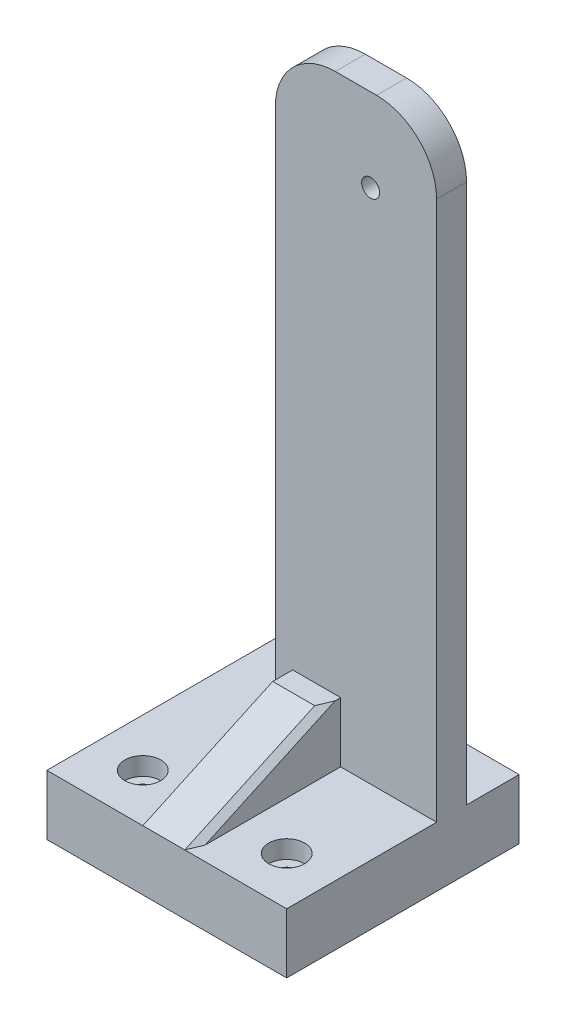
SolidWorks part; units mm, degrees
ref_plane "Front Plane" through (0, 0, 0) normal (0, 0, 1) x (1, 0, 0)
ref_plane "Top Plane" through (0, 0, 0) normal (0, 1, 0) x (1, 0, 0)
ref_plane "Right Plane" through (0, 0, 0) normal (1, 0, 0) x (0, 0, -1)
sketch "Sketch1" plane through (0, 0, 0) normal (0, 1, 0) x (1, 0, 0)
  line L1 (-20, -15) -> (20, -15)
  line L2 (-20, -15) -> (-20, 15)
  line L3 (-20, 15) -> (20, 15)
  line L4 (20, -15) -> (20, 15)
  line L5 (-20, -15) -> (20, 15) construction
  line L6 (-20, 15) -> (20, -15) construction
  line L7 (-20, 15) -> (20, 15)
  line L8 (-20, 15) -> (-20, 9.2)
  line L9 (-20, 9.2) -> (20, 9.2)
  line L10 (20, 15) -> (20, 9.2)
  point P0 (0, 0)
  dimension "D1" = 40
  dimension "D2" = 30
extrude "Boss-Extrude1" add sketch "Sketch1" along normal blind 10 contours L9 L2 L1 L4 | L2 L9 L4 L3
sketch "Sketch2" plane through (0, 10, 0) normal (0, 1, 0) x (1, 0, 0)
  line L0 (20, -15) -> (20, 15) construction
  line L1 (-6.8887, 15) -> (20, 15)
  line L2 (-6.8887, 15) -> (-6.8887, 10)
  line L3 (-6.8887, 10) -> (20, 10)
  line L4 (20, 15) -> (20, 10)
  line L5 (-20, 15) -> (20, 15) construction
  dimension "D1" = 5
  dimension "D2" = 0
extrude "Boss-Extrude2" add sketch "Sketch2" along normal blind 100
sketch "Sketch3" plane through (0, 0, -10) normal (0, 0, 1) x (1, 0, 0)
  line L1 (20, 110) -> (20, 10) construction
  line L2 (-6.8887, 10) -> (20, 10) construction
  circle A0 centre (9, 96.14) radius 1.5
  dimension "D1" = 3
  dimension "D2" = 86.14
  dimension "D3" = 11
extrude "Cut-Extrude1" cut sketch "Sketch3" against normal blind 30
sketch "Sketch6" plane through (0, 10, 0) normal (0, 1, 0) x (1, 0, 0)
  line L0 (-6.8887, 10) -> (20, 10) construction
  line L1 (-4, 10) -> (4, 10)
  line L2 (-4, 10) -> (-4, -15)
  line L3 (-4, -15) -> (4, -15)
  line L4 (4, 10) -> (4, -15)
  line L5 (-20, -15) -> (20, -15) construction
  line L6 (20, -15) -> (20, 10) construction
  line L7 (-20, -15) -> (-20, 15) construction
  dimension "D1" = 16
  dimension "D2" = 16
extrude "Boss-Extrude3" add sketch "Sketch6" along normal blind 10
sketch "Sketch7" plane through (-4, 0, 0) normal (-1, 0, 0) x (0, 0, 1)
  line L0 (-10, 21.5351) -> (15, 10)
  line L2 (-10, 21.5351) -> (15, 21.5351)
  line L3 (15, 21.5351) -> (15, 10)
  line L4 (-10, 20) -> (-10, 10) construction
  line L5 (15, 20) -> (15, 10) construction
extrude "Cut-Extrude4" cut sketch "Sketch7" against normal blind 35
sketch "Sketch8" plane through (0, 0, 0) normal (0, 1, 0) x (1, 0, 0)
  line L0 (-20, 15) -> (4, 15)
  line L1 (-20, 15) -> (4, 15)
  line L2 (-20, 15) -> (-20, 30)
  line L3 (-20, 30) -> (4, 30)
  line L4 (4, 15) -> (4, 30)
  line L6 (20, 15) -> (4, 15)
  line L7 (1.6425, 29.4411) -> (1.5198, 29.4411)
  line L8 (20, 15) -> (20, 23.7683)
  line L9 (20, 23.7683) -> (4, 23.7683)
  line L10 (4, 15) -> (4, 23.7683)
  dimension "D1" = 15
  dimension "D2" = 24
extrude "Boss-Extrude4" add sketch "Sketch8" along normal blind 10
sketch "Sketch9" plane through (0, 10, 0) normal (0, 1, 0) x (1, 0, 0)
  line L0 (-6.8887, 15) -> (20, 15) construction
  line L1 (-4, 15) -> (4, 15)
  line L2 (-4, 15) -> (-4, 30)
  line L3 (-4, 30) -> (4, 30)
  line L4 (4, 15) -> (4, 30)
extrude "Boss-Extrude5" add sketch "Sketch9" along normal blind 30
sketch "Sketch10" plane through (-4, 0, 0) normal (-1, 0, 0) x (0, 0, 1)
  line L0 (-30, 10) -> (-20.1868, 40)
  line L1 (-30, 40) -> (-15, 40) construction
  line L2 (-20.1868, 40) -> (-30, 40)
  line L3 (-30, 40) -> (-30, 10)
extrude "Cut-Extrude5" cut sketch "Sketch10" against normal blind 35
sketch "Sketch11" plane through (0, 10, 0) normal (0, 1, 0) x (1, 0, 0)
  line L0 (-20, -15) -> (-4, -15) construction
  line L1 (4, -15) -> (20, -15) construction
  line L2 (-20, -15) -> (-20, 30) construction
  line L3 (20, -15) -> (20, 10) construction
  circle A0 centre (-12, -7) radius 1.42
  circle A1 centre (12, -7) radius 1.42
  circle A2 centre (-12, 23) radius 1.42
  dimension "D1" = 2.84
  dimension "D2" = 2.84
  dimension "D3" = 2.84
  dimension "D4" = 30
  dimension "D5" = 8
  dimension "D6" = 8
  dimension "D7" = 8
  dimension "D8" = 8
extrude "Cut-Extrude6" cut sketch "Sketch11" against normal blind 20
sketch "Sketch12" plane through (0, 10, 0) normal (0, 1, 0) x (1, 0, 0)
  circle A0 centre (-12, -7) radius 3
  circle A1 centre (12, -7) radius 3
  circle A2 centre (-12, 23) radius 3
  dimension "D1" = 6
  dimension "D2" = 6
  dimension "D3" = 6
extrude "Cut-Extrude7" cut sketch "Sketch12" against normal blind 3
fillet "Fillet1" radius 10 2 edges at (20, 110, -12.5) (-6.8887, 110, -12.5)
chamfer "Chamfer1" distance 1 angle 45 2 edges at (4, 25, -25.0934) (-4, 25, -25.0934)
chamfer "Chamfer2" distance 1 angle 45 1 edges at (4, 15, 4.1635)
